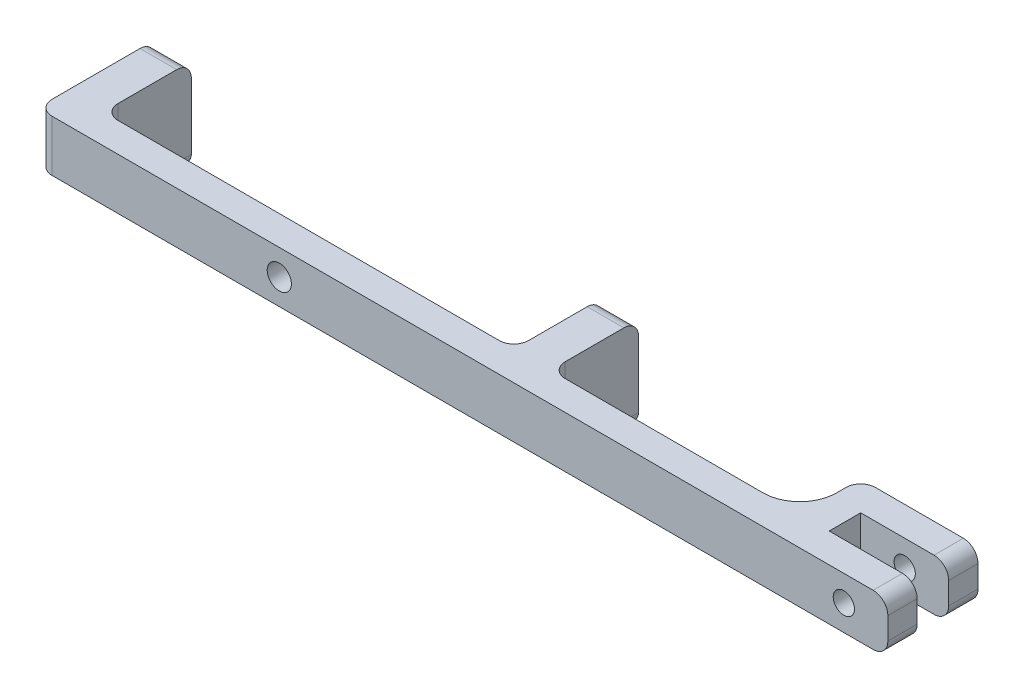
SolidWorks part; units mm, degrees
ref_plane "Front" through (0, 0, 0) normal (0, 0, 1) x (1, 0, 0)
ref_plane "Top" through (0, 0, 0) normal (0, 1, 0) x (1, 0, 0)
ref_plane "Right" through (0, 0, 0) normal (1, 0, 0) x (0, 0, -1)
sketch "Sketch1" plane through (0, 0, 0) normal (0, 1, 0) x (1, 0, 0)
  line L1 (0, 0) -> (66, 0)
  line L2 (0, 0) -> (0, -4)
  line L3 (0, -4) -> (66, -4)
  line L4 (66, 0) -> (66, -4)
  dimension "D1" = 66
  dimension "D2" = 4
extrude "Boss-Extrude1" add sketch "Sketch1" along normal blind 7
sketch "Sketch2" plane through (0, 0, 4) normal (0, 0, 1) x (1, 0, 0)
  line L0 (0, 0) -> (66, 0) construction
  line L1 (66, 7) -> (66, 0) construction
  circle A0 centre (33, 3.5) radius 1.65
  dimension "D1" = 3.3
  dimension "D2" = 3.5
  dimension "D3" = 33
extrude "Cut-Extrude1" cut sketch "Sketch2" against normal through all
sketch "Sketch3" plane through (0, 0, 0) normal (0, 0, -1) x (-1, 0, 0)
  line L0 (-66, 7) -> (-66, 0) construction
  line L1 (-66, 3.5) -> (-61, 3.5)
  line L2 (-66, 3.5) -> (-66, 0)
  line L3 (-66, 0) -> (-61, 0)
  line L4 (-61, 3.5) -> (-61, 0)
  line L5 (-66, 0) -> (0, 0) construction
  line L6 (0, 7) -> (0, 0) construction
  line L7 (0, 3.5) -> (-5, 3.5)
  line L8 (0, 3.5) -> (0, 0)
  line L9 (0, 0) -> (-5, 0)
  line L10 (-5, 3.5) -> (-5, 0)
  dimension "D1" = 5
  dimension "D2" = 5
extrude "Boss-Extrude2" add sketch "Sketch3" along normal blind 12
sketch "Sketch4" plane through (0, 0, 0) normal (0, -1, 0) x (-1, 0, 0)
  line L0 (-61, 12) -> (-61, 0) construction
  line L1 (-66, 12) -> (-61, 12)
  line L2 (-66, 12) -> (-66, 7)
  line L3 (-66, 7) -> (-61, 7)
  line L4 (-61, 12) -> (-61, 7)
  line L5 (0, 12) -> (0, -4) construction
  line L6 (-5, 12) -> (0, 12)
  line L7 (-5, 12) -> (-5, 7)
  line L8 (-5, 7) -> (0, 7)
  line L9 (0, 12) -> (0, 7)
  dimension "D1" = 5
  dimension "D2" = 5
extrude "Boss-Extrude3" add sketch "Sketch4" along normal blind 6
sketch "Sketch5" plane through (66, 0, 0) normal (1, 0, 0) x (0, 0, -1)
  line L1 (-4, 7) -> (0, 7)
  line L2 (-4, 7) -> (-4, 0)
  line L3 (-4, 0) -> (0, 0)
  line L4 (0, 7) -> (0, 0)
extrude "Boss-Extrude4" add sketch "Sketch5" along normal blind 50
sketch "Sketch7" plane through (0, 3.5, 0) normal (0, 1, 0) x (1, 0, 0)
  line L1 (66, 12) -> (61, 12)
  line L2 (66, 12) -> (66, 0)
  line L3 (66, 0) -> (61, 0)
  line L4 (61, 12) -> (61, 0)
  line L5 (5, 12) -> (0, 12)
  line L6 (5, 12) -> (5, 0)
  line L7 (5, 0) -> (0, 0)
  line L8 (0, 12) -> (0, 0)
extrude "Boss-Extrude5" add sketch "Sketch7" along normal blind 3.5
fillet "Fillet1" radius 2 8 edges at (2.5, -6, -12) (0, -6, -9.5) (2.5, -6, -7) (5, -6, -9.5) (63.5, -6, -12) (61, -6, -9.5) (63.5, -6, -7) (66, -6, -9.5)
fillet "Fillet2" radius 2 10 edges at (61, 3.5, 0) (5, 3.5, 0) (63.5, 0, -7) (2.5, 0, -7) (66, 3.5, 0) (116, 0, 2) (116, 7, 2) (0, 3.5, 4) (63.5, 7, -12) (2.5, 7, -12)
sketch "Sketch8" plane through (0, 0, 0) normal (0, 0, -1) x (-1, 0, 0)
  line L0 (-114, 7) -> (-68, 7) construction
  line L1 (-104, 7) -> (-100, 7)
  line L2 (-104, 7) -> (-104, 0)
  line L3 (-104, 0) -> (-100, 0)
  line L4 (-100, 7) -> (-100, 0)
  line L5 (-114, 0) -> (-68, 0) construction
  line L6 (-116, 2) -> (-116, 5) construction
  dimension "D1" = 4
  dimension "D2" = 12
extrude "Boss-Extrude6" add sketch "Sketch8" along normal blind 8.3
sketch "Sketch9" plane through (104, 0, 0) normal (1, 0, 0) x (0, 0, -1)
  line L0 (8.3, 0) -> (0, 0) construction
  line L1 (8.3, 7) -> (4.3, 7)
  line L2 (8.3, 7) -> (8.3, 0)
  line L3 (8.3, 0) -> (4.3, 0)
  line L4 (4.3, 7) -> (4.3, 0)
  dimension "D1" = 4
extrude "Boss-Extrude7" add sketch "Sketch9" along normal blind 12
sketch "Sketch6" plane through (0, 0, 0) normal (0, 0, -1) x (-1, 0, 0)
  line L0 (-116, 2) -> (-116, 5) construction
  line L1 (-116, 7) -> (0, 7) construction
  circle A0 centre (-110, 3.5) radius 1.45
  dimension "D1" = 2.9
  dimension "D2" = 6
  dimension "D3" = 3.5
extrude "Cut-Extrude2" cut sketch "Sketch6" against normal through all both and the other way through all
fillet "Fillet3" radius 2 2 edges at (116, 0, -6.3) (116, 7, -6.3)
fillet "Fillet4" radius 5 1 edges at (100, 3.5, 0)
fillet "Fillet5" radius 2 1 edges at (100, 3.5, -8.3)
equation "\"D3@Sketch2\"=\"D1@Sketch1\"/2"
